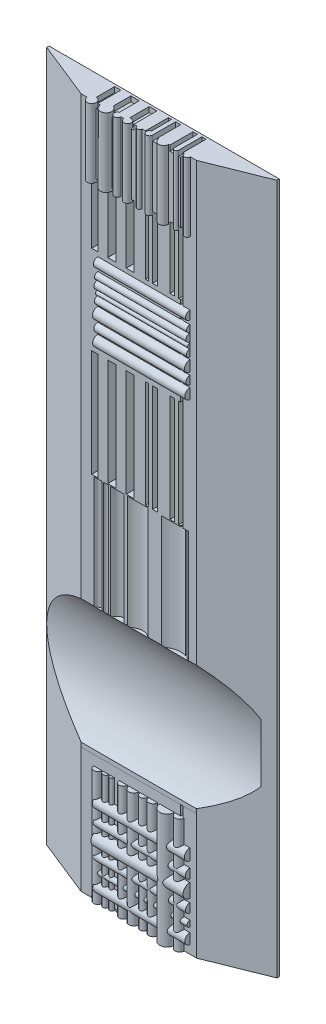
SolidWorks part; units mm, degrees
ref_plane "前视基准面" through (0, 0, 0) normal (0, 0, 1) x (1, 0, 0)
ref_plane "上视基准面" through (0, 0, 0) normal (0, 1, 0) x (1, 0, 0)
ref_plane "右视基准面" through (0, 0, 0) normal (1, 0, 0) x (0, 0, -1)
sketch "草图1" plane through (0, 0, 0) normal (0, 0, 1) x (1, 0, 0)
  line L1 (0, 0) -> (10, 0)
  line L2 (0, 0) -> (0, 30)
  line L3 (0, 30) -> (10, 30)
  line L4 (10, 0) -> (10, 30)
  dimension "D1" = 10
  dimension "D2" = 30
extrude "凸台-拉伸1" add sketch "草图1" along normal blind 0.1
sketch "草图4" plane through (0, 0, 0) normal (0, -1, 0) x (1, 0, 0)
  line L0 (0, 0.1) -> (2.4993, 0.1)
  line L1 (0, 0.1) -> (10, 0.1) construction
  line L2 (2.4993, 0.1) -> (2.4993, 1.1006)
  line L3 (2.4993, 1.1006) -> (0, 0.1)
  line L4 (10, 0.1) -> (7.5007, 0.1)
  line L5 (7.5007, 0.1) -> (7.5007, 1.1006)
  line L6 (7.5007, 1.1006) -> (10, 0.1)
extrude "凸台-拉伸3" add sketch "草图4" against normal blind 30
sketch "草图5" plane through (0, 0, 0.1) normal (0, 0, 1) x (1, 0, 0)
  line L0 (2.4993, 0) -> (7.5007, 0) construction
  line L1 (2.4993, 30) -> (2.9538, 30)
  line L2 (2.4993, 30) -> (2.4993, 0)
  line L3 (2.4993, 0) -> (2.9538, 0)
  line L4 (2.9538, 30) -> (2.9538, 0)
  line L5 (7.5007, 30) -> (2.4993, 30) construction
  line L6 (7.5007, 30) -> (6.9172, 30)
  line L7 (7.5007, 30) -> (7.5007, 0)
  line L8 (7.5007, 0) -> (6.9172, 0)
  line L9 (6.9172, 30) -> (6.9172, 0)
  line L10 (6.351, 0) -> (5.8181, 0)
  line L11 (6.351, 0) -> (6.351, 30)
  line L12 (6.351, 30) -> (5.8181, 30)
  line L13 (5.8181, 0) -> (5.8181, 30)
  line L15 (5.2852, 30) -> (4.7857, 30)
  line L16 (5.2852, 30) -> (5.2852, 0)
  line L17 (5.2852, 0) -> (4.7857, 0)
  line L18 (4.7857, 30) -> (4.7857, 0)
  line L19 (4.4526, 0) -> (4.0196, 0)
  line L20 (4.4526, 0) -> (4.4526, 30)
  line L21 (4.4526, 30) -> (4.0196, 30)
  line L22 (4.0196, 0) -> (4.0196, 30)
  line L23 (3.6533, 30) -> (3.2203, 30)
  line L24 (3.6533, 30) -> (3.6533, 0)
  line L25 (3.6533, 0) -> (3.2203, 0)
  line L26 (3.2203, 30) -> (3.2203, 0)
  line L27 (6.5448, 30) -> (6.7335, 30)
  line L28 (6.5448, 30) -> (6.5448, 0)
  line L29 (6.5448, 0) -> (6.7335, 0)
  line L30 (6.7335, 30) -> (6.7335, 0)
extrude "凸台-拉伸4" add sketch "草图5" along normal blind 1
sketch "草图6" plane through (0, 0, 0.1) normal (0, 0, 1) x (1, 0, 0)
  line L0 (5.8181, 30) -> (5.2852, 30) construction
  line L1 (5.4226, 30) -> (5.5961, 30)
  line L2 (5.4226, 30) -> (5.4226, 0.0068)
  line L3 (5.4226, 0.0068) -> (5.5961, 0.0068)
  line L4 (5.5961, 30) -> (5.5961, 0.0068)
extrude "凸台-拉伸5" add sketch "草图6" along normal blind 1
sketch "草图8" plane through (0, 0, 0) normal (0, 0, -1) x (-1, 0, 0)
  line L1 (-2.9533, 5.4296) -> (-6.8178, 5.4296)
  line L2 (-2.9533, 5.4296) -> (-2.9533, 0.0863)
  line L3 (-2.9533, 0.0863) -> (-6.8178, 0.0863)
  line L4 (-6.8178, 5.4296) -> (-6.8178, 0.0863)
  line L5 (-2.9533, 10.8773) -> (-6.8178, 10.8773)
  line L6 (-2.9533, 10.8773) -> (-2.9533, 15.9201)
  line L7 (-2.9533, 15.9201) -> (-6.8178, 15.9201)
  line L8 (-6.8178, 10.8773) -> (-6.8178, 15.9201)
  line L9 (-6.8178, 20.5688) -> (-2.9533, 20.5688)
  line L10 (-6.8178, 20.5688) -> (-6.8178, 24.4209)
  line L11 (-6.8178, 24.4209) -> (-2.9533, 24.4209)
  line L12 (-2.9533, 20.5688) -> (-2.9533, 24.4209)
  line L13 (-2.9533, 29.7719) -> (-6.8178, 29.7719)
  line L14 (-2.9533, 29.7719) -> (-2.9533, 27.1225)
  line L15 (-2.9533, 27.1225) -> (-6.8178, 27.1225)
  line L16 (-6.8178, 29.7719) -> (-6.8178, 27.1225)
extrude "凸台-拉伸6" add sketch "草图8" against normal blind 1.1
sketch "草图9" plane through (3.2203, 0, 0) normal (-1, 0, 0) x (0, 0, 1)
  line L0 (1.1, 0) -> (1.1, 30) construction
  line L1 (1.1006, 30) -> (1.1006, 0) construction
  line L2 (1.1, 30) -> (1.1, 0) construction
  circle A0 centre (1.1, 3.7663) radius 0.2406
  circle A1 centre (1.1, 3.0491) radius 0.2029
  circle A2 centre (1.1006, 2.4075) radius 0.2979
  circle A3 centre (1.1, 1.747) radius 0.1925
  circle A4 centre (1.1006, 1.1619) radius 0.1302
  circle A5 centre (1.1, 0.5958) radius 0.2226
  circle A18 centre (1.1, 24.0446) radius 0.1918
  circle A19 centre (1.1, 23.5365) radius 0.1463
  circle A20 centre (1.1, 23.2021) radius 0.1709
  circle A21 centre (1.1, 22.6221) radius 0.155
  circle A22 centre (1.1, 22.9015) radius 0.0999
  circle A23 centre (1.1, 22.1352) radius 0.2345
  circle A24 centre (1.1, 21.5998) radius 0.1765
  circle A25 centre (1.1006, 21.0939) radius 0.225
extrude "凸台-拉伸7" add sketch "草图9" against normal blind 4
sketch "草图10" plane through (0, 0, 0) normal (0, -1, 0) x (1, 0, 0)
  line L0 (3.2203, 1.1) -> (6.8178, 1.1) construction
  line L1 (4.0196, 1.1) -> (3.6533, 1.1) construction
  line L2 (4.7857, 1.1) -> (5.2852, 1.1) construction
  line L3 (4.7857, 1.1) -> (4.4526, 1.1) construction
  line L4 (6.8178, 1.1) -> (6.7335, 1.1) construction
  circle A0 centre (3.2203, 1.1) radius 0.1771
  circle A1 centre (3.5718, 1.1) radius 0.1292
  circle A2 centre (3.8364, 1.1) radius 0.1009
  circle A3 centre (4.3284, 1.1) radius 0.1765
  circle A4 centre (4.7857, 1.1) radius 0.2159
  circle A5 centre (5.2321, 1.1) radius 0.1749
  circle A6 centre (5.6258, 1.1) radius 0.1931
  circle A7 centre (6.2286, 1.1) radius 0.3162
  circle A8 centre (6.7757, 1.1) radius 0.1972
extrude "凸台-拉伸10" add sketch "草图10" against normal blind 5 separate body
sketch "草图11" plane through (0, 30, 0) normal (0, 1, 0) x (1, 0, 0)
  line L0 (3.6533, -1.1) -> (3.2203, -1.1) construction
  line L1 (4.4526, -1.1) -> (4.0196, -1.1) construction
  line L2 (6.8178, -1.1) -> (3.2203, -1.1) construction
  line L3 (5.2852, -1.1) -> (4.7857, -1.1) construction
  line L4 (6.351, -1.1) -> (5.8181, -1.1) construction
  line L5 (6.7335, -1.1) -> (6.5448, -1.1) construction
  line L6 (7.5007, -1.1) -> (6.9172, -1.1) construction
  circle A0 centre (2.9538, -1.1) radius 0.1964
  circle A1 centre (3.5803, -1.1) radius 0.245
  circle A2 centre (4.0733, -1.1) radius 0.1453
  circle A3 centre (4.5154, -1.1) radius 0.1588
  circle A4 centre (5.0355, -1.1) radius 0.1052
  circle A5 centre (5.4591, -1.1) radius 0.137
  circle A6 centre (6.0846, -1.1) radius 0.2149
  circle A7 centre (6.6392, -1.1) radius 0.0943
  circle A8 centre (7.1083, -1.1) radius 0.1302
extrude "凸台-拉伸11" add sketch "草图11" against normal blind 3
sketch "草图12" plane through (0, 10.8773, 0) normal (0, -1, 0) x (1, 0, 0)
  line L0 (3.2203, 1.1) -> (6.8178, 1.1) construction
  circle A0 centre (3.2203, 1.1) radius 0.1771
  circle A1 centre (3.5718, 1.1) radius 0.102
  circle A2 centre (4.0648, 1.1) radius 0.289
  circle A3 centre (4.949, 1.4549) radius 0.5712
  circle A4 centre (6.5728, 1.6759) radius 0.819
extrude "切除-拉伸1" cut sketch "草图12" against normal blind 5
sketch "草图13" plane through (0, 5.4296, 0) normal (0, 1, 0) x (1, 0, 0)
  line L0 (10, 0) -> (0, 0) construction
  line L1 (2.4993, -1.1006) -> (7.4739, -1.1006)
  line L2 (2.4993, -1.1006) -> (2.4993, 0)
  line L3 (2.4993, 0) -> (7.4739, 0)
  line L4 (7.4739, -1.1006) -> (7.4739, 0)
extrude "凸台-拉伸12" add sketch "草图13" along normal blind 5.5
sketch "草图14" plane through (0, 0, 0) normal (1, 0, 0) x (0, 0, -1)
  circle A0 centre (-4.2397, 8.3164) radius 4.1397
extrude "切除-拉伸2" cut sketch "草图14" along normal blind 9.5 and the other way blind 1
